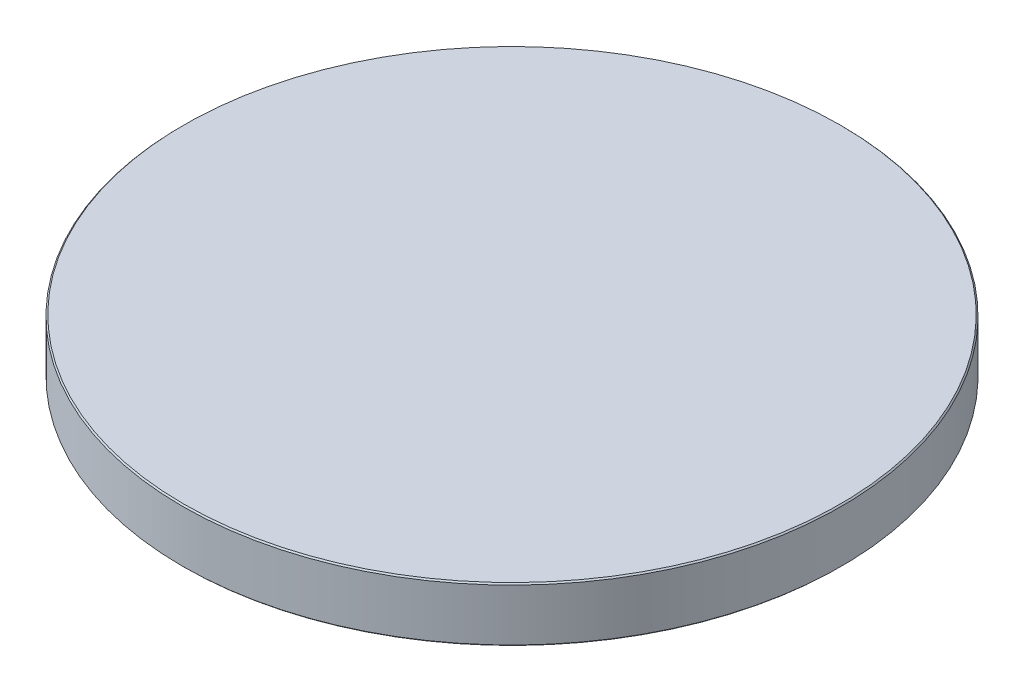
SolidWorks part; units mm, degrees
ref_plane "Front Plane" through (0, 0, 0) normal (0, 0, 1) x (1, 0, 0)
ref_plane "Top Plane" through (0, 0, 0) normal (0, 1, 0) x (1, 0, 0)
ref_plane "Right Plane" through (0, 0, 0) normal (1, 0, 0) x (0, 0, -1)
sketch "Sketch1" plane through (0, 0, 0) normal (0, 1, 0) x (1, 0, 0)
  circle A0 centre (0, 0) radius 12.7
extrude "Boss-Extrude1" add sketch "Sketch1" along normal blind 2.1
chamfer "Chamfer1" distance 0.05 angle 45 2 edges at (0, 2.1, 12.7) (0, 0, 12.7)
